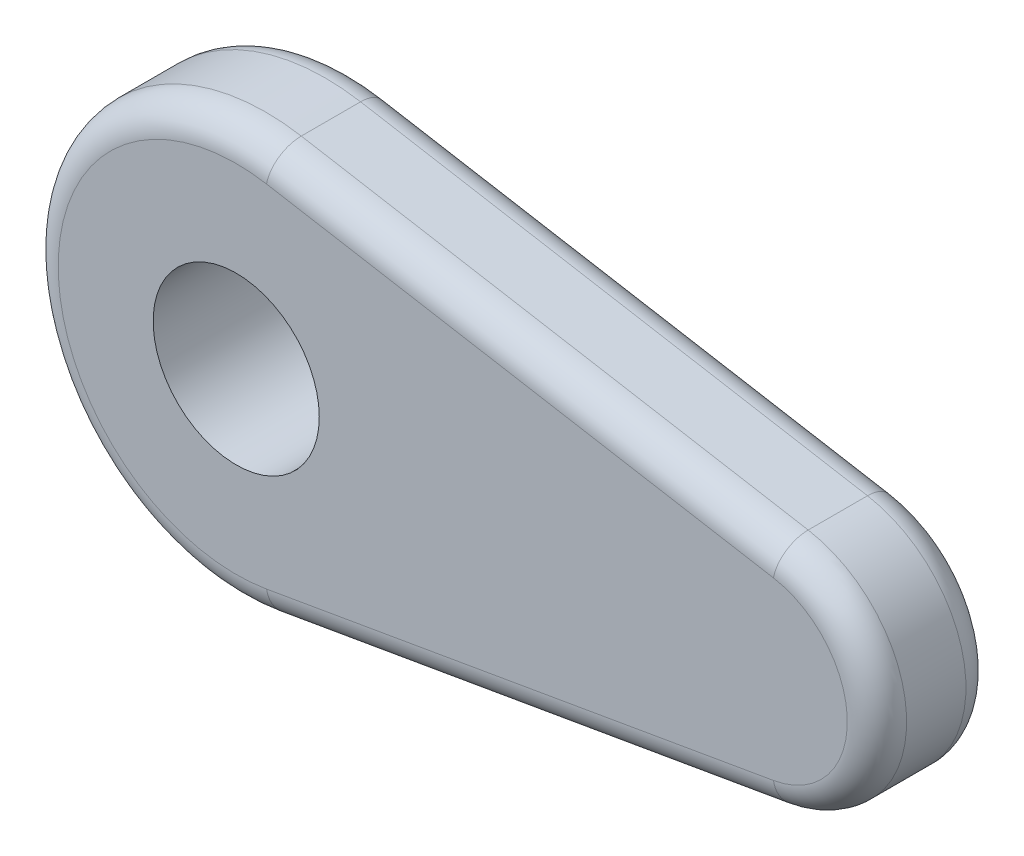
SolidWorks part; units mm, degrees
ref_plane "前视基准面" through (0, 0, 0) normal (0, 0, 1) x (1, 0, 0)
ref_plane "上视基准面" through (0, 0, 0) normal (0, 1, 0) x (1, 0, 0)
ref_plane "右视基准面" through (0, 0, 0) normal (1, 0, 0) x (0, 0, -1)
sketch "草图1" plane through (0, 0, 0) normal (0, 0, 1) x (1, 0, 0)
  line L0 (-38.6271, 0) -> (29.3729, 0) construction
  line L1 (-32.6612, 34.4878) -> (52.782, 19.7073)
  line L2 (-32.6612, -34.4878) -> (52.782, -19.7073)
  line L3 (39.3729, 0) -> (49.3729, 0) construction
  arc A0 (-32.6612, 34.4878) -> (-32.6612, -34.4878) centre (-38.6271, 0) ccw
  arc A1 (52.782, -19.7073) -> (52.782, 19.7073) centre (49.3729, 0) ccw
  circle A2 centre (-38.6271, 0) radius 14
  dimension "D2" = 70
  dimension "D3" = 28
extrude "凸台-拉伸1" add sketch "草图1" along normal blind 20
fillet "圆角1" radius 5 4 edges at (10.0604, 27.0976, 20) (69.3729, 0, 20) (10.0604, -27.0976, 20) (-73.6271, 0, 20)
fillet "圆角2" radius 5 4 edges at (10.0604, 27.0976, 0) (69.3729, 0, 0) (10.0604, -27.0976, 0) (-73.6271, 0, 0)
